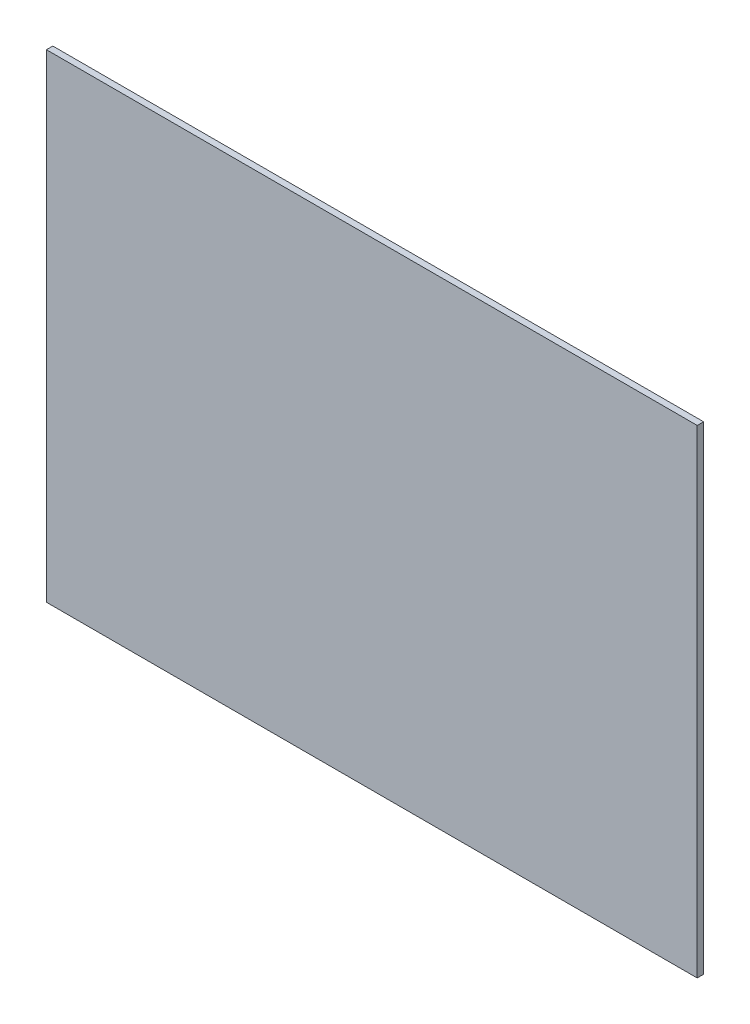
SolidWorks part; units mm, degrees
ref_plane "Front Plane" through (0, 0, 0) normal (0, 0, 1) x (1, 0, 0)
ref_plane "Top Plane" through (0, 0, 0) normal (0, 1, 0) x (1, 0, 0)
ref_plane "Right Plane" through (0, 0, 0) normal (1, 0, 0) x (0, 0, -1)
sketch "Sketch1" plane through (0, 0, 0) normal (0, 0, 1) x (1, 0, 0)
  line L0 (-98.233, 36.8011) -> (105.767, 36.8011)
  line L1 (105.767, 36.8011) -> (105.767, -113.1989)
  line L2 (105.767, -113.1989) -> (-98.233, -113.1989)
  line L3 (-98.233, -113.1989) -> (-98.233, 36.8011)
  dimension "D1" = 204
  dimension "D2" = 150
extrude "Boss-Extrude1" add sketch "Sketch1" along normal blind 2
